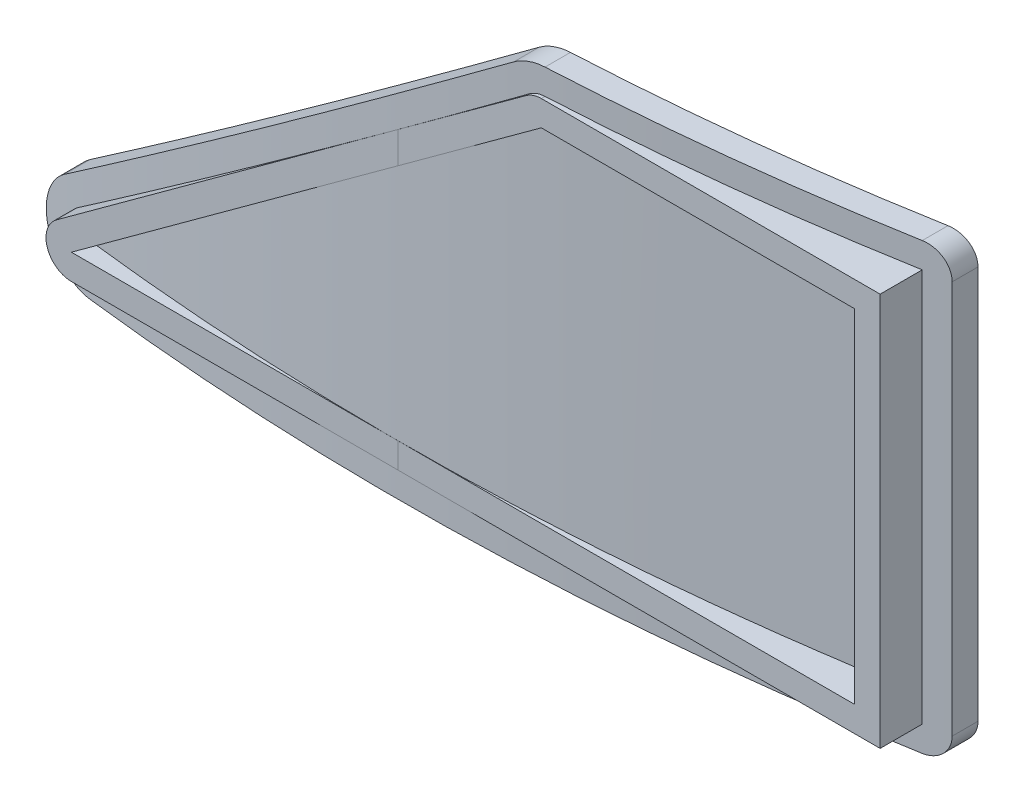
SolidWorks part; units mm, degrees
ref_plane "Front Plane" through (0, 0, 0) normal (0, 0, 1) x (1, 0, 0)
ref_plane "Top Plane" through (0, 0, 0) normal (0, 1, 0) x (1, 0, 0)
ref_plane "Right Plane" through (0, 0, 0) normal (1, 0, 0) x (0, 0, -1)
sketch "Sketch1" plane through (0, 0, 0) normal (0, 1, 0) x (1, 0, 0)
  line L0 (-200, -1068.4423) -> (-200, -1078.6144)
  line L1 (200, -1068.4423) -> (200, -1078.6144)
  arc A0 (-200, -1068.4423) -> (200, -1068.4423) centre (0, 0) ccw
  arc A1 (-200, -1078.6144) -> (200, -1078.6144) centre (0, 0) ccw
  point P10 (-15.6089, -1.4869)
  dimension "D1" = 2194
  dimension "D2" = 10
  dimension "D3" = 200
  dimension "D4" = 400
extrude "Boss-Extrude1" add sketch "Sketch1" along normal blind 175
fillet "Fillet1" radius 10 4 edges at (200, 0, 1073.5284) (200, 175, 1073.5284) (-200, 0, 1073.5284) (-200, 175, 1073.5284)
sketch "Sketch4" plane through (0, 0, 0) normal (0, 0, 1) x (1, 0, 0)
  line L0 (-190, 0) -> (50, 175)
  line L1 (-190, 0) -> (190, 0) construction
  line L2 (190, 175) -> (-190, 175) construction
  line L3 (50, 175) -> (200, 175)
  line L4 (200, 175) -> (200, 0)
  line L5 (200, 0) -> (-190, 0)
  line L6 (200, 165) -> (200, 10) construction
  line L7 (-200, 165) -> (-200, 10) construction
  point P10 (0, 0)
  dimension "D1" = 250
extrude "Cut-Extrude3" cut sketch "Sketch4" against normal through all both and the other way through all flip side to cut
fillet "Fillet4" radius 20 2 edges at (-190, 0, 1075.3433) (50, 175, 1090.8547)
ref_plane "Plane3" through (0, 0, 1097) normal (0, 0, 1) x (1, 0, 0)
sketch "Sketch5" plane through (0, 0, 1097) normal (0, 0, 1) x (1, 0, 0)
  line L20 (56.5174, 155) -> (-128.6255, 20)
  line L21 (-128.6255, 20) -> (180, 20)
  line L22 (180, 20) -> (180, 155)
  line L23 (180, 155) -> (56.5174, 155)
  line L24 (50.6256, 163.0801) -> (-134.5172, 28.0801)
  line L25 (-128.6255, 10) -> (190, 10)
  line L26 (190, 10) -> (190, 165)
  line L27 (190, 165) -> (56.5174, 165)
  line L28 (50.6256, 163.0801) -> (-134.5172, 28.0801)
  line L29 (-128.6255, 10) -> (190, 10)
  line L30 (190, 10) -> (190, 165)
  line L31 (190, 165) -> (56.5174, 165)
  arc A16 (-128.6255, 20) -> (-128.6255, 20) centre (-128.6255, 20) ccw
  arc A17 (56.5174, 155) -> (56.5174, 155) centre (56.5174, 155) ccw
  arc A20 (-134.5172, 28.0801) -> (-128.6255, 10) centre (-128.6255, 20) ccw
  arc A21 (56.5174, 165) -> (50.6256, 163.0801) centre (56.5174, 155) ccw
  arc A22 (-134.5172, 28.0801) -> (-128.6255, 10) centre (-128.6255, 20) ccw
  arc A23 (56.5174, 165) -> (50.6256, 163.0801) centre (56.5174, 155) ccw
  dimension "D1" = 10
  dimension "D2" = 10
extrude "Boss-Extrude3" add sketch "Sketch5" against normal up to surface (14.8683 mm away) separate body
